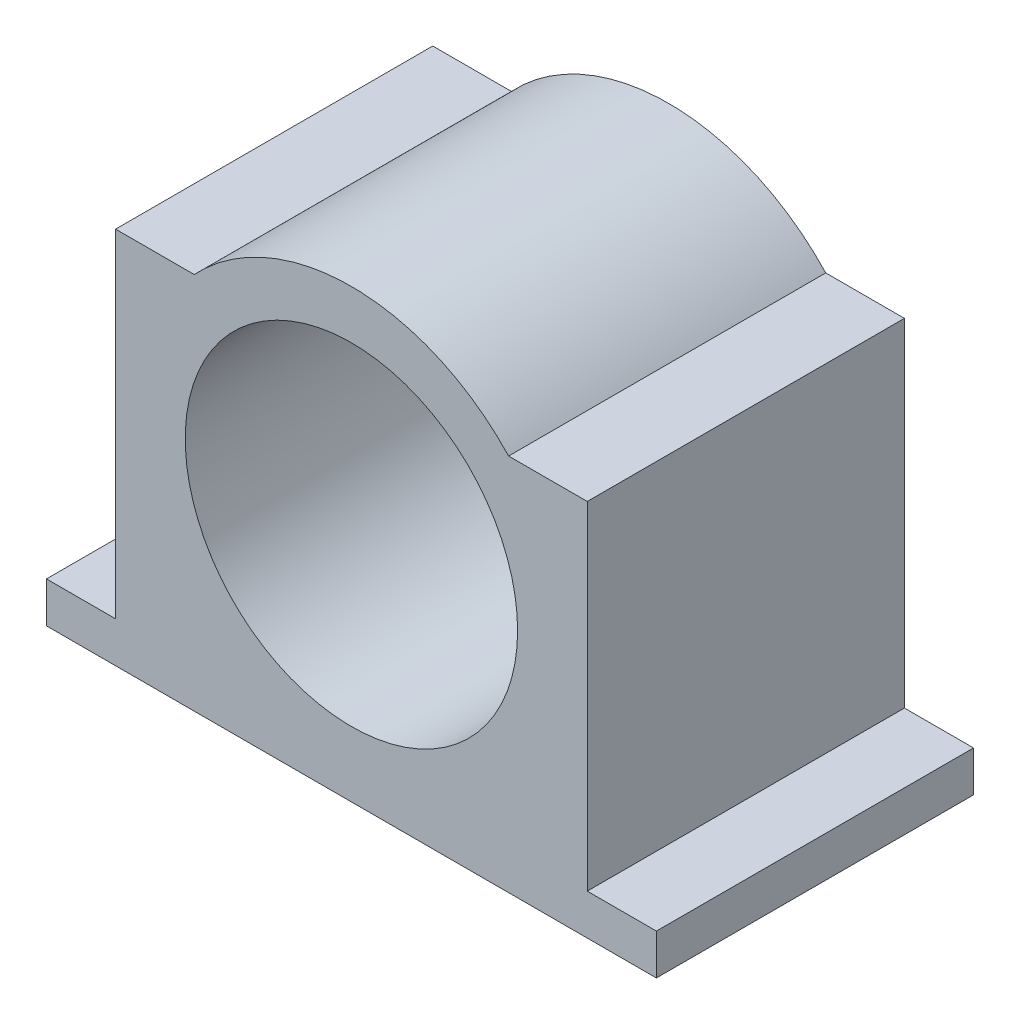
SolidWorks part; units mm, degrees
material "6063-O, Barre extrudée (SS)"
ref_plane "Plan de face" through (0, 0, 0) normal (0, 0, 1) x (1, 0, 0)
ref_plane "Plan de dessus" through (0, 0, 0) normal (0, 1, 0) x (1, 0, 0)
ref_plane "Plan de droite" through (0, 0, 0) normal (1, 0, 0) x (0, 0, -1)
sketch "Esquisse1" plane through (0, 0, 0) normal (0, 0, 1) x (1, 0, 0)
  line L0 (0, 0) -> (150, 0)
  line L1 (150, 0) -> (150, 9.9977)
  line L2 (150, 9.9977) -> (133, 9.9977)
  line L3 (133, 9.9977) -> (133, 92.9977)
  line L4 (133, 92.9977) -> (113.6528, 92.9977)
  line L5 (17, 93) -> (17, 10)
  line L6 (17, 10) -> (0, 10)
  line L7 (0, 10) -> (0, 0)
  line L8 (75, 0) -> (75, 107.1953) construction
  line L9 (36.3493, 93) -> (17, 93)
  circle A0 centre (75, 56.9227) radius 40.872
  arc A1 (36.3493, 93) -> (113.6528, 92.9977) centre (75, 56.9227) cw
  dimension "D6" = 58
  dimension "D1" = 150
  dimension "D2" = 9.9977
  dimension "D3" = 17
  dimension "D4" = 83
  dimension "D5" = 116
  dimension "D8" = 83
  dimension "D9" = 10
extrude "Boss.-Extru.1" add sketch "Esquisse1" along normal blind 78
